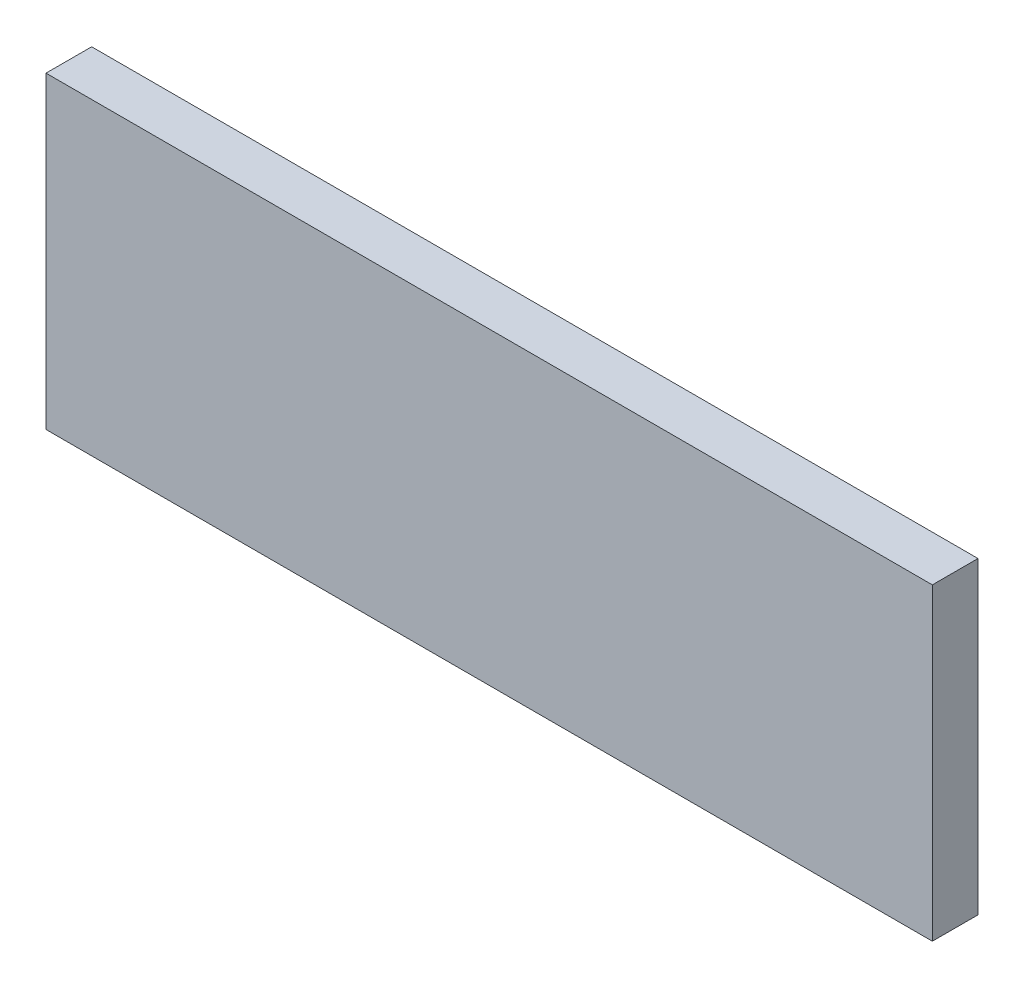
SolidWorks part; units mm, degrees
ref_plane "Front Plane" through (0, 0, 0) normal (0, 0, 1) x (1, 0, 0)
ref_plane "Top Plane" through (0, 0, 0) normal (0, 1, 0) x (1, 0, 0)
ref_plane "Right Plane" through (0, 0, 0) normal (1, 0, 0) x (0, 0, -1)
sketch "Sketch2" plane through (0, 0, 0) normal (0, 0, 1) x (1, 0, 0)
  line L1 (-46.228, -16.0972) -> (46.228, -16.0972)
  line L2 (-46.228, -16.0972) -> (-46.228, 16.0973)
  line L3 (-46.228, 16.0973) -> (46.228, 16.0973)
  line L4 (46.228, -16.0972) -> (46.228, 16.0973)
  line L5 (-46.228, -16.0972) -> (46.228, 16.0973) construction
  line L6 (-46.228, 16.0973) -> (46.228, -16.0972) construction
  point P0 (0, 0)
  dimension "D1" = 92.456
  dimension "D2" = 32.1945
extrude "Boss-Extrude1" add sketch "Sketch2" along normal blind 4.7625
